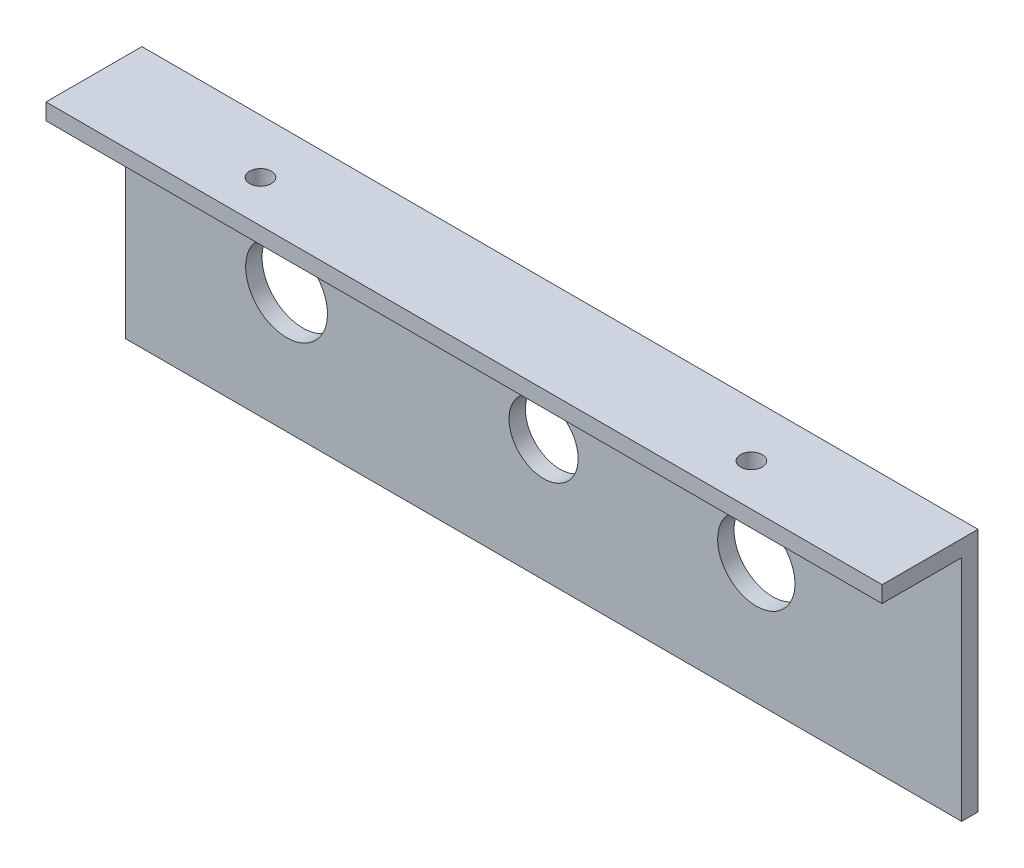
SolidWorks part; units mm, degrees
ref_plane "Plan de face" through (0, 0, 0) normal (0, 0, 1) x (1, 0, 0)
ref_plane "Plan de dessus" through (0, 0, 0) normal (0, 1, 0) x (1, 0, 0)
ref_plane "Plan de droite" through (0, 0, 0) normal (1, 0, 0) x (0, 0, -1)
sketch "Esquisse1" plane through (0, 0, 0) normal (0, 0, 1) x (1, 0, 0)
  line L1 (-64.897, 18.9992) -> (64.897, 18.9992)
  line L2 (-64.897, 18.9992) -> (-64.897, -18.9992)
  line L3 (-64.897, -18.9992) -> (64.897, -18.9992)
  line L4 (64.897, 18.9992) -> (64.897, -18.9992)
  point P4 (-64.897, 0)
  point P5 (0, -18.9992)
  dimension "D1" = 37.9984
  dimension "D2" = 129.794
extrude "Boss.-Extru.1" add sketch "Esquisse1" along normal blind 2.54 contours L3 L4 L1 L2
sketch "Esquisse2" plane through (-64.897, 0, 0) normal (-1, 0, 0) x (0, 0, 1)
  line L1 (2.54, 18.9992) -> (14.8844, 18.9992)
  line L2 (2.54, 18.9992) -> (2.54, 16.4592)
  line L3 (2.54, 16.4592) -> (14.8844, 16.4592)
  line L4 (14.8844, 18.9992) -> (14.8844, 16.4592)
  dimension "D1" = 12.3444
  dimension "D2" = 2.54
extrude "Boss.-Extru.2" add sketch "Esquisse2" against normal blind 129.794 contours L1 L4 L3 L2
sketch "Esquisse3" plane through (0, 0, 2.54) normal (0, 0, 1) x (1, 0, 0)
  circle A0 centre (0, 0) radius 5.3658
  dimension "D1" = 10.7315
extrude "Enlèv. mat.-Extru.1" cut sketch "Esquisse3" against normal through all
sketch "Esquisse4" plane through (0, 18.9992, 0) normal (0, 1, 0) x (1, 0, 0)
  line L0 (-38.1, -8.382) -> (38.1, -8.382) construction
  line L3 (-64.897, 0) -> (64.897, 0) construction
  circle A0 centre (-38.1, -8.382) radius 1.6827
  circle A1 centre (38.1, -8.382) radius 1.6827
  point P4 (0, -8.382)
  dimension "D1" = 3.3655
  dimension "D2" = 76.2
  dimension "D3" = 8.382
extrude "Enlèv. mat.-Extru.2" cut sketch "Esquisse4" against normal through all
sketch "Esquisse5" plane through (0, 0, 2.54) normal (0, 0, 1) x (1, 0, 0)
  line L1 (-64.897, 18.9992) -> (-64.897, -18.9992) construction
  circle A0 centre (-39.897, 0) radius 6.35
  dimension "D1" = 12.7
  dimension "D2" = 25
extrude "Enlèv. mat.-Extru.3" cut sketch "Esquisse5" against normal blind 2.54 contours A0
sketch "Esquisse7" plane through (0, 0, 0) normal (0, 0, -1) x (-1, 0, 0)
  line L0 (-33.02, 0) -> (0, 0) construction
  line L1 (0, 0) -> (39.74, -0.0508) construction
  line L2 (39.74, 0.9492) -> (39.74, -1.0508) construction
  circle A0 centre (-33.02, 0) radius 6
  point P4 (0, 0)
  point P8 (-40.8176, 0)
  dimension "D1" = 12
  dimension "D2" = 33.02
extrude "Enlèv. mat.-Extru.4" cut sketch "Esquisse7" against normal blind 2.54 contours A0
